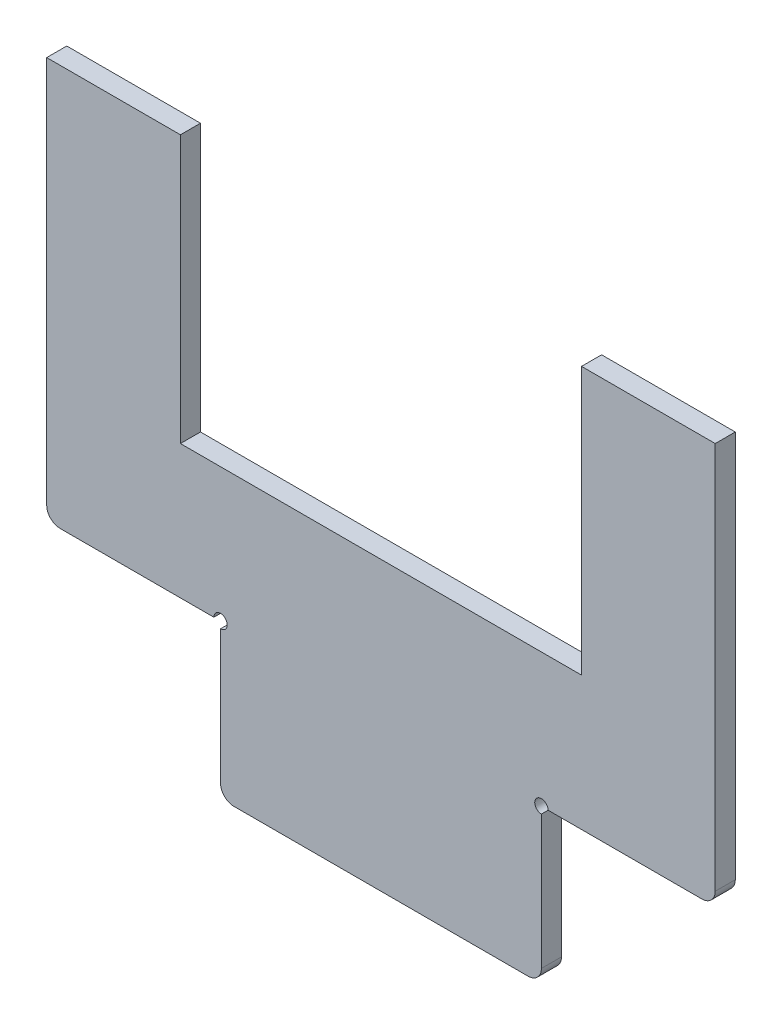
SolidWorks part; units mm, degrees
material "Thornel Mat VMA"
ref_plane "Front Plane" through (0, 0, 0) normal (0, 0, 1) x (1, 0, 0)
ref_plane "Top Plane" through (0, 0, 0) normal (0, 1, 0) x (1, 0, 0)
ref_plane "Right Plane" through (0, 0, 0) normal (1, 0, 0) x (0, 0, -1)
sketch "Sketch1" plane through (0, 0, 0) normal (0, 0, 1) x (1, 0, 0)
  line L0 (0, 11.5) -> (0, 0) construction
  line L1 (-24, -11.5) -> (24, -11.5)
  line L2 (-24, -11.5) -> (-24, 11.5)
  line L3 (-24, 11.5) -> (24, 11.5)
  line L4 (24, -11.5) -> (24, 11.5)
  line L5 (-24, -11.5) -> (24, 11.5) construction
  line L6 (-24, 11.5) -> (24, -11.5) construction
  point P0 (0, 0)
  dimension "D1" = 23
  dimension "D2" = 48
extrude "Boss-Extrude1" add sketch "Sketch1" along normal blind 3
sketch "Sketch2" plane through (0, 0, 3) normal (0, 0, 1) x (1, 0, 0)
  line L0 (0, 11.5) -> (0, 0) construction
  line L1 (24, 11.5) -> (-24, 11.5) construction
  line L3 (50, 11.5) -> (-50, 11.5)
  line L4 (0, 11.5) -> (0, 31.5) construction
  line L5 (30, 31.5) -> (-30, 31.5)
  line L8 (-50, 11.5) -> (-50, 71.5)
  line L9 (-50, 71.5) -> (-30, 71.5)
  line L10 (-30, 31.5) -> (-30, 71.5)
  line L11 (30, 31.5) -> (30, 71.5)
  line L12 (50, 71.5) -> (30, 71.5)
  line L13 (50, 11.5) -> (50, 71.5)
  point P8 (-12.9273, 25.5091)
  point P9 (-40.4812, 16.8985)
  point P10 (0, 0)
  point P14 (0, 0)
  point P15 (-10.023, 20.1314)
  point P16 (-30, 28.7342)
  dimension "D1" = 50
  dimension "D2" = 20
  dimension "D3" = 60
  dimension "D4" = 20
extrude "Boss-Extrude2" add sketch "Sketch2" against normal up to surface (3 mm away) up to face at (0, 0, 0)
sketch "Sketch3" plane through (0, 0, 3) normal (0, 0, 1) x (1, 0, 0)
  circle A0 centre (-24, 11.5) radius 1
  circle A1 centre (24, 11.5) radius 1
  dimension "D1" = 2
extrude "Cut-Extrude1" cut sketch "Sketch3" against normal through all
fillet "Fillet1" radius 2 4 edges at (50, 11.5, 1.5) (-50, 11.5, 1.5) (24, -11.5, 1.5) (-24, -11.5, 1.5)
